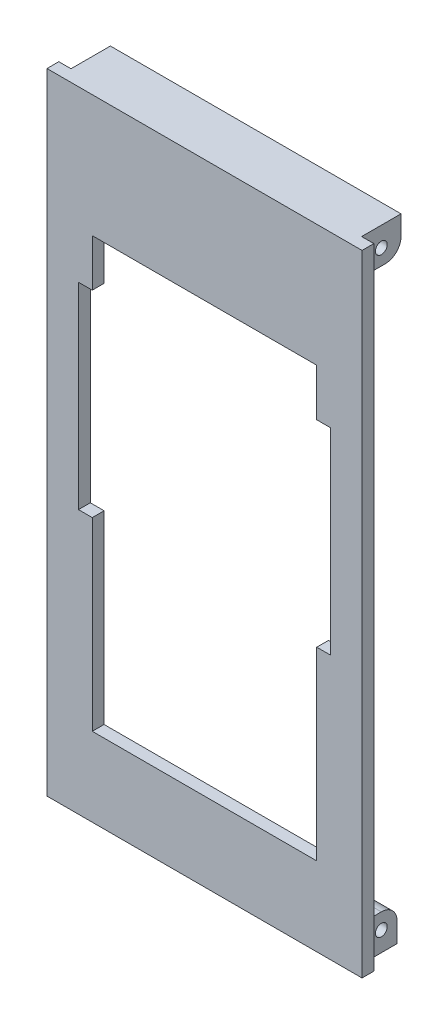
SolidWorks part; units mm, degrees
ref_plane "Front Plane" through (0, 0, 0) normal (0, 0, 1) x (1, 0, 0)
ref_plane "Top Plane" through (0, 0, 0) normal (0, 1, 0) x (1, 0, 0)
ref_plane "Right Plane" through (0, 0, 0) normal (1, 0, 0) x (0, 0, -1)
sketch "Sketch3" plane through (0, 0, 0) normal (1, 0, 0) x (0, 0, -1)
  line L0 (0, 160) -> (13, 160)
  line L2 (0, 0) -> (0, 160)
  line L4 (3, 9) -> (3, 151)
  line L7 (3, 151) -> (13, 151)
  line L8 (13, 160) -> (13, 151)
  line L11 (3, 9) -> (12, 9)
  line L12 (12, 0) -> (12, 9)
  line L13 (0, 0) -> (12, 0)
  circle A0 centre (8, 155) radius 1.5
  circle A1 centre (8, 5) radius 1.5
  dimension "D2" = 3
  dimension "D3" = 3
  dimension "D1" = 3
  dimension "D4" = 160
  dimension "D5" = 5
  dimension "D6" = 8
  dimension "D7" = 4
  dimension "D8" = 4
  dimension "D9" = 5
  dimension "D10" = 8
  dimension "D11" = 4
  dimension "D12" = 5
extrude "Boss-Extrude3" add sketch "Sketch3" along normal blind 80 separate body
sketch "Sketch4" plane through (0, 0, 0) normal (0, 0, 1) x (1, 0, 0)
  line L0 (0, 0) -> (80, 0) construction
  line L1 (40, 0) -> (40, 184) construction
  line L2 (11.5, 117) -> (11.5, 129)
  line L3 (11.5, 20) -> (68.5, 20)
  line L4 (11.5, 20) -> (11.5, 67)
  line L5 (11.5, 129) -> (68.5, 129)
  line L6 (68.5, 20) -> (68.5, 67)
  line L7 (11.5, 20) -> (68.5, 129) construction
  line L8 (11.5, 129) -> (68.5, 20) construction
  line L9 (8, 67) -> (11.5, 67)
  line L10 (8, 67) -> (8, 117)
  line L11 (8, 117) -> (11.5, 117)
  line L12 (72, 67) -> (72, 117)
  line L13 (8, 67) -> (72, 117) construction
  line L14 (8, 117) -> (72, 67) construction
  line L15 (68.5, 117) -> (72, 117)
  line L16 (68.5, 117) -> (68.5, 129)
  line L17 (68.5, 67) -> (72, 67)
  line L18 (80, 160) -> (0, 160) construction
  point P6 (40, 74.5)
  point P11 (40, 92)
  dimension "D1" = 31
  dimension "D2" = 20
  dimension "D3" = 3.5
  dimension "D4" = 12
  dimension "D5" = 50
  dimension "D6" = 57
extrude "Cut-Extrude1" cut sketch "Sketch4" against normal through all
sketch "Sketch5" plane through (0, 0, 0) normal (0, 1, 0) x (1, 0, 0)
  line L0 (0, 0) -> (80, 0) construction
  line L1 (80, 3) -> (76.9, 3)
  line L2 (40, 0) -> (40, 22.0256) construction
  line L3 (0, 15) -> (3.1, 15)
  line L4 (0, 15) -> (0, 3)
  line L5 (0, 3) -> (3.1, 3)
  line L6 (3.1, 15) -> (3.1, 3)
  line L7 (76.9, 15) -> (76.9, 3)
  line L8 (80, 15) -> (76.9, 15)
  line L9 (80, 15) -> (80, 3)
  dimension "D1" = 3
  dimension "D2" = 3.1
  dimension "D3" = 12
extrude "Cut-Extrude2" cut sketch "Sketch5" along normal through all contours L4 L5 L6 L3 | L1 L7 L8 L9
fillet "Fillet1" radius 4 2 edges at (40, 151, -13) (40, 9, -12)
